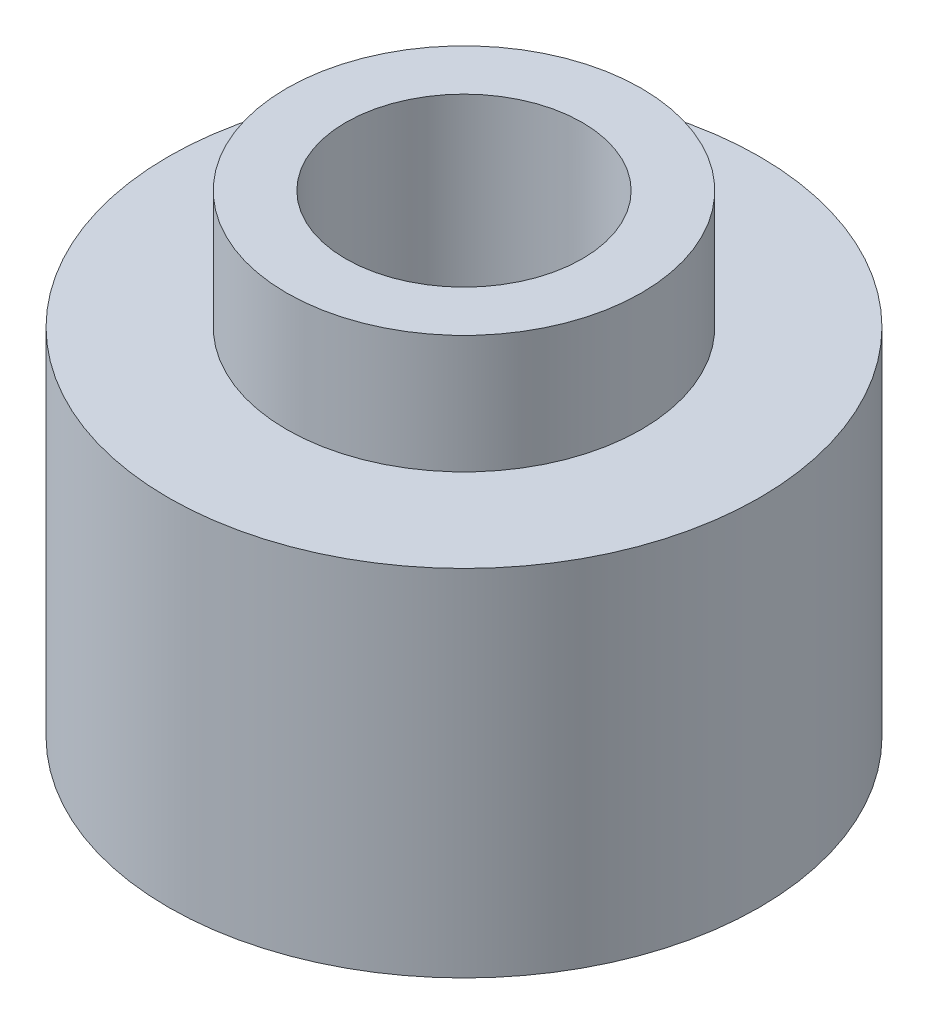
SolidWorks part; units mm, degrees
ref_plane "Front Plane" through (0, 0, 0) normal (0, 0, 1) x (1, 0, 0)
ref_plane "Top Plane" through (0, 0, 0) normal (0, 1, 0) x (1, 0, 0)
ref_plane "Right Plane" through (0, 0, 0) normal (1, 0, 0) x (0, 0, -1)
sketch "Sketch1" plane through (0, 0, 0) normal (0, 1, 0) x (1, 0, 0)
  circle A0 centre (0, 0) radius 7.9375
  dimension "D1" = 15.875
extrude "Boss-Extrude1" add sketch "Sketch1" along normal blind 9.525
sketch "Sketch2" plane through (0, 9.525, 0) normal (0, 1, 0) x (1, 0, 0)
  circle A0 centre (0, 0) radius 4.7625
  dimension "D1" = 9.525
extrude "Boss-Extrude2" add sketch "Sketch2" along normal blind 3.175 contours A0
hole_wizard "1/4 (0.25) Diameter Hole1" positions "Sketch4" profile "Sketch5" hole size "1/4" standard "ANSI Inch" end condition through all
sketch "Sketch4" plane through (0, 0, 0) normal (0, -1, 0) x (-1, 0, 0)
  point P0 (0, 0)
sketch "Sketch5" plane through (0, 0, 0) normal (1, 0, 0) x (0, 0, -1)
  line L0 (0, 0) -> (0, 12.7)
  line L1 (0, 12.7) -> (3.175, 12.7)
  line L2 (3.175, 12.7) -> (3.175, 0)
  line L5 (3.175, 0) -> (0, 0)
  line L11 (0, -6.35) -> (0, 107.95) construction
  dimension "Thru Hole Dia." = 6.35
  dimension "Thru Hole Depth" = 12.7
ref_plane "Plane1" through (0, 0, -7.9375) normal (0, 0, -1) x (-1, 0, 0)
hole_wizard "#10-32 Tapped Hole1" positions "Sketch7" profile "Sketch6" tap size "#10-32" standard "ANSI Inch"
sketch "Sketch7" plane through (0, 0, -7.9375) normal (0, 0, -1) x (-1, 0, 0)
  line L0 (0, 0) -> (0, 9.525) construction
  line L2 (7.9375, 9.525) -> (-7.9375, 9.525) construction
  point P0 (0, 4.7625)
sketch "Sketch6" plane through (0, 4.7625, -7.9375) normal (1, 0, 0) x (0, 1, 0)
  line L0 (0, 0) -> (0, 4.7625)
  line L1 (0, 4.7625) -> (2.0193, 4.7625)
  line L2 (2.0193, 4.7625) -> (2.0193, 0)
  line L5 (2.0193, 0) -> (0, 0)
  line L11 (0, -6.35) -> (0, 107.95) construction
  dimension "Thru Tap Drill Dia." = 4.0386
  dimension "Thru Tap Drill Depth" = 4.7625
cosmetic thread "Hole Thread1" parameters "D2"=4.826
